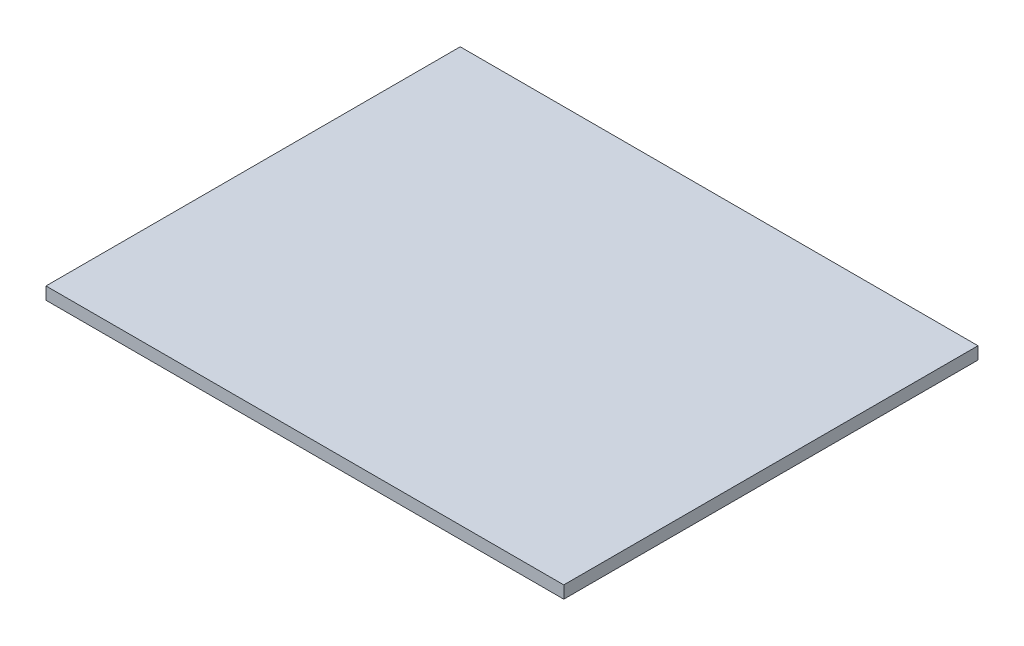
SolidWorks part; units mm, degrees
ref_plane "Front Plane" through (0, 0, 0) normal (0, 0, 1) x (1, 0, 0)
ref_plane "Top Plane" through (0, 0, 0) normal (0, 1, 0) x (1, 0, 0)
ref_plane "Right Plane" through (0, 0, 0) normal (1, 0, 0) x (0, 0, -1)
sketch "Sketch1" plane through (0, 0, 0) normal (0, 1, 0) x (1, 0, 0)
  line L1 (-12.5, -10) -> (12.5, -10)
  line L2 (-12.5, -10) -> (-12.5, 10)
  line L3 (-12.5, 10) -> (12.5, 10)
  line L4 (12.5, -10) -> (12.5, 10)
  line L5 (-12.5, -10) -> (12.5, 10) construction
  line L6 (-12.5, 10) -> (12.5, -10) construction
  point P0 (0, 0)
  dimension "D1" = 25
  dimension "D2" = 20
extrude "Boss-Extrude1" add sketch "Sketch1" along normal blind 0.6
